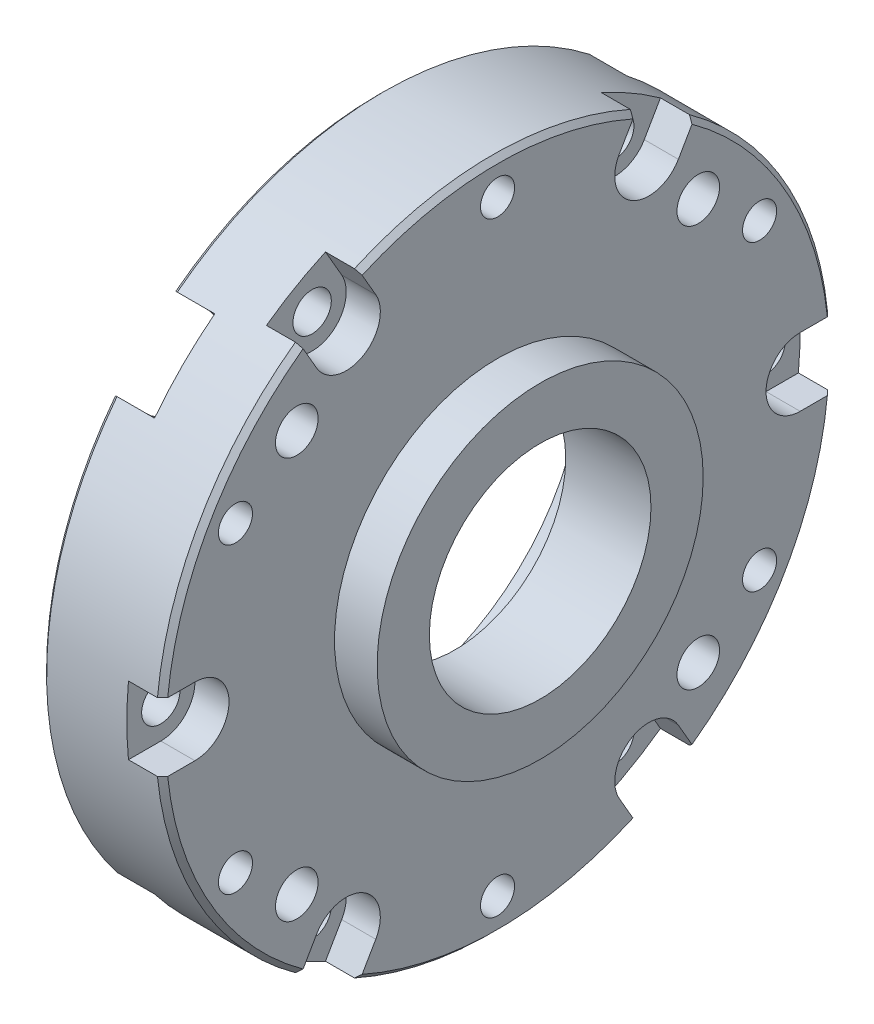
SolidWorks part; units mm, degrees
ref_plane "前视基准面" through (0, 0, 0) normal (0, 0, 1) x (1, 0, 0)
ref_plane "上视基准面" through (0, 0, 0) normal (0, 1, 0) x (1, 0, 0)
ref_plane "右视基准面" through (0, 0, 0) normal (1, 0, 0) x (0, 0, -1)
sketch "草图1" plane through (0, 0, 0) normal (1, 0, 0) x (0, 0, -1)
  circle A0 centre (0, 0) radius 39.5
extrude "凸台-拉伸1" add sketch "草图1" along normal blind 14 contours A0
sketch "草图2" plane through (0, 0, 0) normal (-1, 0, 0) x (0, 0, 1)
  circle A0 centre (-35.5, 0) radius 2.25
  circle A1 centre (-30.7439, 17.75) radius 2
  circle A2 centre (-17.75, 30.7439) radius 2.25
  circle A3 centre (0, 35.5) radius 2
  circle A4 centre (17.75, 30.7439) radius 2.25
  circle A5 centre (30.7439, 17.75) radius 2
  circle A6 centre (35.5, 0) radius 2.25
  circle A7 centre (30.7439, -17.75) radius 2
  circle A8 centre (17.75, -30.7439) radius 2.25
  circle A9 centre (0, -35.5) radius 2
  circle A10 centre (-17.75, -30.7439) radius 2.25
  circle A11 centre (-30.7439, -17.75) radius 2
extrude "切除-拉伸1" cut sketch "草图2" against normal blind 16
sketch "草图4" plane through (14, 0, 0) normal (1, 0, 0) x (0, 0, -1)
  line L0 (-35.5, 4) -> (-44.2011, 4)
  line L1 (-44.2011, 4) -> (-44.2011, -4)
  line L2 (-44.2011, -4) -> (-35.5, -4)
  arc A0 (-35.5, -4) -> (-35.5, 4) centre (-35.5, 0) ccw
extrude "切除-拉伸2" cut sketch "草图4" against normal blind 4
sketch "草图7" plane through (14, 0, 0) normal (1, 0, 0) x (0, 0, -1)
  line L5 (-21.2141, -28.7439) -> (-24.6163, -34.6367)
  line L6 (-24.6163, -34.6367) -> (-17.6881, -38.6367)
  line L7 (-17.6881, -38.6367) -> (-14.2859, -32.7439)
  line L8 (14.2859, -32.7439) -> (17.5983, -38.4811)
  line L9 (17.5983, -38.4811) -> (24.5265, -34.4811)
  line L10 (24.5265, -34.4811) -> (21.2141, -28.7439)
  line L11 (35.5, -4) -> (41.3051, -4)
  line L12 (41.3051, -4) -> (41.3051, 4)
  line L13 (41.3051, 4) -> (35.5, 4)
  line L14 (21.2141, 28.7439) -> (23.9572, 33.4951)
  line L15 (23.9572, 33.4951) -> (17.029, 37.4951)
  line L16 (17.029, 37.4951) -> (14.2859, 32.7439)
  line L17 (-14.2859, 32.7439) -> (-17.029, 37.4951)
  line L18 (-17.029, 37.4951) -> (-23.9572, 33.4951)
  line L19 (-23.9572, 33.4951) -> (-21.2141, 28.7439)
  arc A0 (-14.2859, -32.7439) -> (-21.2141, -28.7439) centre (-17.75, -30.7439) ccw
  arc A1 (21.2141, -28.7439) -> (14.2859, -32.7439) centre (17.75, -30.7439) ccw
  arc A2 (35.5, 4) -> (35.5, -4) centre (35.5, 0) ccw
  arc A3 (14.2859, 32.7439) -> (21.2141, 28.7439) centre (17.75, 30.7439) ccw
  arc A4 (-21.2141, 28.7439) -> (-14.2859, 32.7439) centre (-17.75, 30.7439) ccw
extrude "切除-拉伸3" cut sketch "草图7" against normal blind 4
sketch "草图8" plane through (0, 0, 0) normal (-1, 0, 0) x (0, 0, 1)
  circle A0 centre (0, 0) radius 24.05
extrude "切除-拉伸4" cut sketch "草图8" against normal blind 9
sketch "草图9" plane through (14, 0, 0) normal (1, 0, 0) x (0, 0, -1)
  circle A0 centre (23.55, -23.55) radius 2.5
  circle A1 centre (-23.55, -23.55) radius 2.5
  circle A2 centre (-23.55, 23.55) radius 2.5
  circle A3 centre (23.55, 23.55) radius 2.5
extrude "切除-拉伸5" cut sketch "草图9" against normal blind 15
sketch "草图10" plane through (14, 0, 0) normal (1, 0, 0) x (0, 0, -1)
  circle A0 centre (0, 0) radius 19.125
extrude "凸台-拉伸2" add sketch "草图10" along normal blind 5
sketch "草图11" plane through (19, 0, 0) normal (1, 0, 0) x (0, 0, -1)
  circle A0 centre (0, 0) radius 13
extrude "切除-拉伸6" cut sketch "草图11" against normal blind 104
sketch "草图12" plane through (0, 0, 0) normal (-1, 0, 0) x (0, 0, 1)
  line L4 (20.0145, -27.0855) -> (26.014, -33.0851)
  line L5 (26.014, -33.0851) -> (33.0851, -26.014)
  line L6 (33.0851, -26.014) -> (27.0855, -20.0145)
  line L7 (27.0855, 20.0145) -> (32.9303, 25.8593)
  line L8 (32.9303, 25.8593) -> (25.8593, 32.9303)
  line L9 (25.8593, 32.9303) -> (20.0145, 27.0855)
  line L10 (-20.0145, 27.0855) -> (-27.2901, 34.3612)
  line L11 (-27.2901, 34.3612) -> (-34.3612, 27.2901)
  line L12 (-34.3612, 27.2901) -> (-27.0855, 20.0145)
  line L13 (-27.0855, -20.0145) -> (-33.9712, -26.9001)
  line L14 (-33.9712, -26.9001) -> (-26.9001, -33.9712)
  line L15 (-26.9001, -33.9712) -> (-20.0145, -27.0855)
  arc A1 (27.0855, -20.0145) -> (20.0145, -27.0855) centre (23.55, -23.55) ccw
  arc A2 (20.0145, 27.0855) -> (27.0855, 20.0145) centre (23.55, 23.55) ccw
  arc A3 (-27.0855, 20.0145) -> (-20.0145, 27.0855) centre (-23.55, 23.55) ccw
  arc A4 (-20.0145, -27.0855) -> (-27.0855, -20.0145) centre (-23.55, -23.55) ccw
extrude "切除-拉伸7" cut sketch "草图12" against normal blind 5
chamfer "倒角2" distance 0.6 angle 45 1 edges at (0, 0, -39.5)
chamfer "倒角3" distance 0.6 angle 45 1 edges at (0, -39.5, 0)
chamfer "倒角4" distance 0.6 angle 45 1 edges at (0, 0, 39.5)
chamfer "倒角5" distance 0.6 angle 45 1 edges at (0, 39.5, 0)
chamfer "倒角6" distance 0.6 angle 45 1 edges at (14, 19.75, -34.208)
chamfer "倒角7" distance 0.6 angle 45 1 edges at (14, 39.5, 0)
chamfer "倒角9" distance 0.6 angle 45 1 edges at (14, -19.75, -34.208)
chamfer "倒角10" distance 0.6 angle 45 1 edges at (14, -39.5, 0)
chamfer "倒角11" distance 0.6 angle 45 1 edges at (14, -19.75, 34.208)
chamfer "倒角12" distance 0.6 angle 45 1 edges at (14, 19.75, 34.208)
